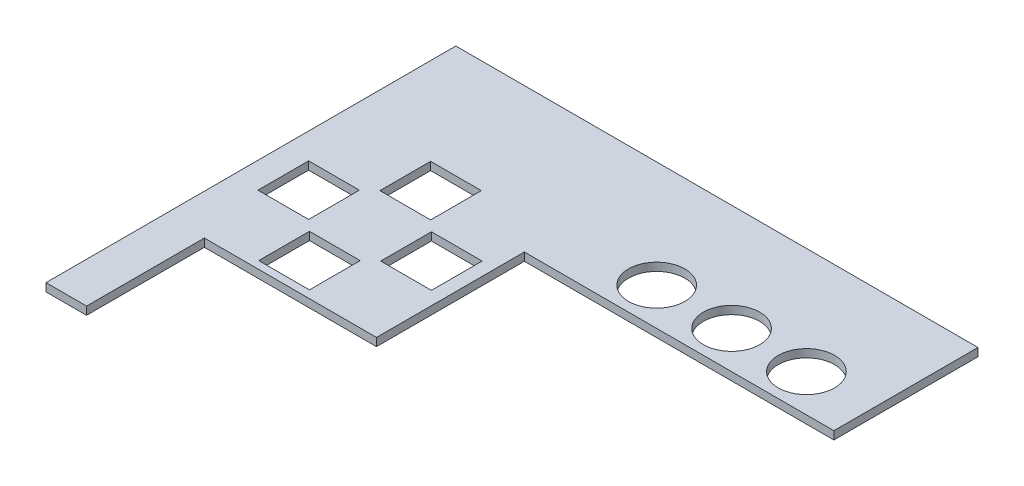
SolidWorks part; units mm, degrees
ref_plane "Front Plane" through (0, 0, 0) normal (0, 0, 1) x (1, 0, 0)
ref_plane "Top Plane" through (0, 0, 0) normal (0, 1, 0) x (1, 0, 0)
ref_plane "Right Plane" through (0, 0, 0) normal (1, 0, 0) x (0, 0, -1)
sketch "Sketch1" plane through (0, 0, 0) normal (0, 1, 0) x (1, 0, 0)
  line L1 (32.425, -25.45) -> (-32.425, -25.45)
  line L2 (32.425, -25.45) -> (32.425, 25.45)
  line L3 (32.425, 25.45) -> (-32.425, 25.45)
  line L4 (-32.425, -25.45) -> (-32.425, 25.45)
  line L5 (32.425, -25.45) -> (-32.425, 25.45) construction
  line L6 (32.425, 25.45) -> (-32.425, -25.45) construction
  point P0 (0, 0)
extrude "Boss-Extrude1" add sketch "Sketch1" along normal blind 1
sketch "Sketch2" plane through (0, 1, 0) normal (0, 1, 0) x (1, 0, 0)
  line L0 (-22.9118, 0.8052) -> (-13.9618, 0.8052) construction
  line L1 (-29.2118, 3.9552) -> (-22.9118, 3.9552)
  line L2 (-29.2118, 3.9552) -> (-29.2118, -2.3448)
  line L3 (-29.2118, -2.3448) -> (-22.9118, -2.3448)
  line L4 (-22.9118, 3.9552) -> (-22.9118, -2.3448)
  line L5 (-29.2118, 3.9552) -> (-22.9118, -2.3448) construction
  line L6 (-29.2118, -2.3448) -> (-22.9118, 3.9552) construction
  line L11 (-7.6618, -2.3448) -> (-13.9618, -2.3448)
  line L12 (-13.9618, 3.9552) -> (-13.9618, -2.3448)
  line L13 (-21.5868, 11.4802) -> (-15.2868, 11.4802)
  line L14 (-7.6618, 3.9552) -> (-13.9618, 3.9552)
  line L15 (-7.6618, 3.9552) -> (-7.6618, -2.3448)
  line L16 (-15.2868, 5.1802) -> (-15.2868, 11.4802)
  line L21 (-18.4368, 5.1802) -> (-18.4368, -3.5698) construction
  line L22 (-21.5868, 5.1802) -> (-15.2868, 5.1802)
  line L23 (-21.5868, 5.1802) -> (-21.5868, 11.4802)
  line L24 (-21.5868, -3.5698) -> (-15.2868, -3.5698)
  line L25 (-21.5868, -3.5698) -> (-21.5868, -9.8698)
  line L26 (-21.5868, -9.8698) -> (-15.2868, -9.8698)
  line L27 (-15.2868, -3.5698) -> (-15.2868, -9.8698)
  line L28 (-18.4368, -3.5698) -> (-18.4368, -9.8698) construction
  line L29 (-32.425, 0.8052) -> (12.1436, 0.8052) construction
  line L30 (-32.425, 25.45) -> (-32.425, -25.45) construction
  circle A0 centre (-26.0618, 0.8052) radius 2.25
  circle A1 centre (-10.8118, 0.8052) radius 2.25
  circle A2 centre (-18.4368, -6.7198) radius 2.25
  circle A3 centre (-18.4368, 8.3302) radius 2.25
  point P0 (-26.0618, 0.8052)
sketch "Sketch3" plane through (0, 1, 0) normal (0, 1, 0) x (1, 0, 0)
  line L0 (0.0283, 25.4449) -> (0.0283, -25.4551) construction
  circle A9 centre (5.7666, 12.2001) radius 3.5
  circle A10 centre (15.0666, 12.2001) radius 3.5
  circle A11 centre (24.3666, 12.2001) radius 3.5
extrude "Cut-Extrude1" cut sketch "Sketch2" against normal blind 10
extrude "Cut-Extrude2" cut sketch "Sketch3" against normal blind 10
sketch "Sketch5" plane through (0, 1, 0) normal (0, 1, 0) x (1, 0, 0)
  line L0 (0, 25.45) -> (0, -25.45) construction
  line L1 (32.425, 25.45) -> (-32.425, 25.45) construction
  line L2 (-32.425, -25.45) -> (32.425, -25.45) construction
  line L3 (-7.6618, 0.8052) -> (5.7382, 0.8052)
  line L4 (-7.6618, -2.3448) -> (-7.6618, 3.9552) construction
  line L5 (5.7382, 0.8052) -> (5.7382, 12.2052)
sketch "Sketch6" plane through (0, 1, 0) normal (0, 1, 0) x (1, 0, 0)
  line L0 (-6.0137, -10.8182) -> (-6.0137, 7.5498)
  line L2 (32.425, -25.45) -> (32.425, 25.45) construction
  line L3 (-6.0137, 7.5498) -> (32.425, 7.5498)
  line L4 (-32.425, -25.45) -> (32.425, -25.45) construction
  line L5 (-27.3886, -25.45) -> (-27.3886, -10.8182)
  line L8 (-27.3886, -25.45) -> (32.425, -25.45)
  line L9 (32.425, 7.5498) -> (32.425, -25.45)
  line L10 (-27.3886, -10.8182) -> (-6.0137, -10.8182)
extrude "Cut-Extrude3" cut sketch "Sketch6" against normal blind 10
